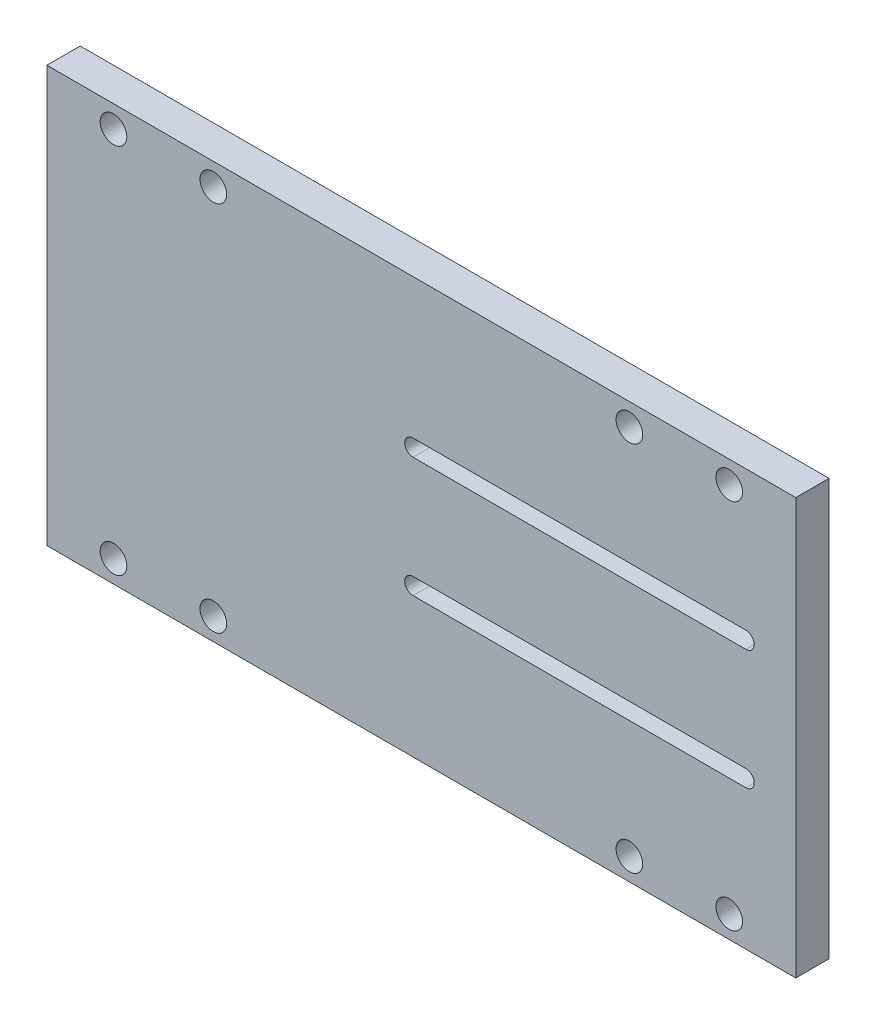
SolidWorks part; units mm, degrees
ref_plane "Front Plane" through (0, 0, 0) normal (0, 0, 1) x (1, 0, 0)
ref_plane "Top Plane" through (0, 0, 0) normal (0, 1, 0) x (1, 0, 0)
ref_plane "Right Plane" through (0, 0, 0) normal (1, 0, 0) x (0, 0, -1)
sketch "Sketch1" plane through (0, 0, 0) normal (0, 0, 1) x (1, 0, 0)
  line L1 (0, 0) -> (114.3, 0)
  line L2 (0, 0) -> (0, 63.5)
  line L3 (0, 63.5) -> (114.3, 63.5)
  line L4 (114.3, 0) -> (114.3, 63.5)
extrude "Boss-Extrude3" add sketch "Sketch1" along normal blind 5.08
sketch "Sketch2" plane through (0, 0, 0) normal (0, 0, 1) x (1, 0, 0)
  line L0 (57.15, 63.5) -> (57.15, 60.1218) construction
  line L1 (114.3, 63.5) -> (0, 63.5) construction
  line L2 (57.15, 60.1218) -> (114.3, 60.1218) construction
  line L3 (114.3, 0) -> (114.3, 63.5) construction
  line L5 (114.3, 31.75) -> (0, 31.75) construction
  line L6 (0, 63.5) -> (0, 0) construction
  circle A0 centre (88.9, 60.1218) radius 2.032
  circle A1 centre (88.9, 3.3782) radius 2.032
  circle A2 centre (25.4, 3.3782) radius 2.032
  circle A3 centre (25.4, 60.1218) radius 2.032
  circle A4 centre (10.16, 3.3782) radius 2.032
  circle A5 centre (10.16, 60.1218) radius 2.032
  circle A6 centre (104.14, 3.3782) radius 2.032
  circle A7 centre (104.14, 60.1218) radius 2.032
extrude "Cut-Extrude4" cut sketch "Sketch2" along normal through all
sketch "Sketch3" plane through (0, 0, 0) normal (0, 0, -1) x (-1, 0, 0)
  line L0 (-106.68, 31.75) -> (-106.68, 40.894) construction
  line L1 (-106.68, 31.75) -> (-81.28, 31.75) construction
  line L2 (-81.28, 31.75) -> (-81.28, 63.5) construction
  line L3 (-106.68, 31.75) -> (-114.3, 31.75) construction
  line L4 (-114.3, 0) -> (-114.3, 63.5) construction
  line L5 (-114.3, 63.5) -> (0, 63.5) construction
  line L6 (-81.28, 63.5) -> (-81.28, 0) construction
  line L7 (0, 0) -> (-114.3, 0) construction
  line L8 (-106.68, 42.164) -> (-55.88, 42.164)
  line L9 (-106.68, 39.624) -> (-55.88, 39.624)
  line L10 (-106.68, 23.876) -> (-55.88, 23.876)
  line L11 (-106.68, 21.336) -> (-55.88, 21.336)
  arc A0 (-106.68, 42.164) -> (-106.68, 39.624) centre (-106.68, 40.894) ccw
  arc A1 (-106.68, 21.336) -> (-106.68, 23.876) centre (-106.68, 22.606) cw
  arc A2 (-55.88, 21.336) -> (-55.88, 23.876) centre (-55.88, 22.606) ccw
  arc A3 (-55.88, 42.164) -> (-55.88, 39.624) centre (-55.88, 40.894) cw
extrude "Cut-Extrude5" cut sketch "Sketch3" against normal through all
